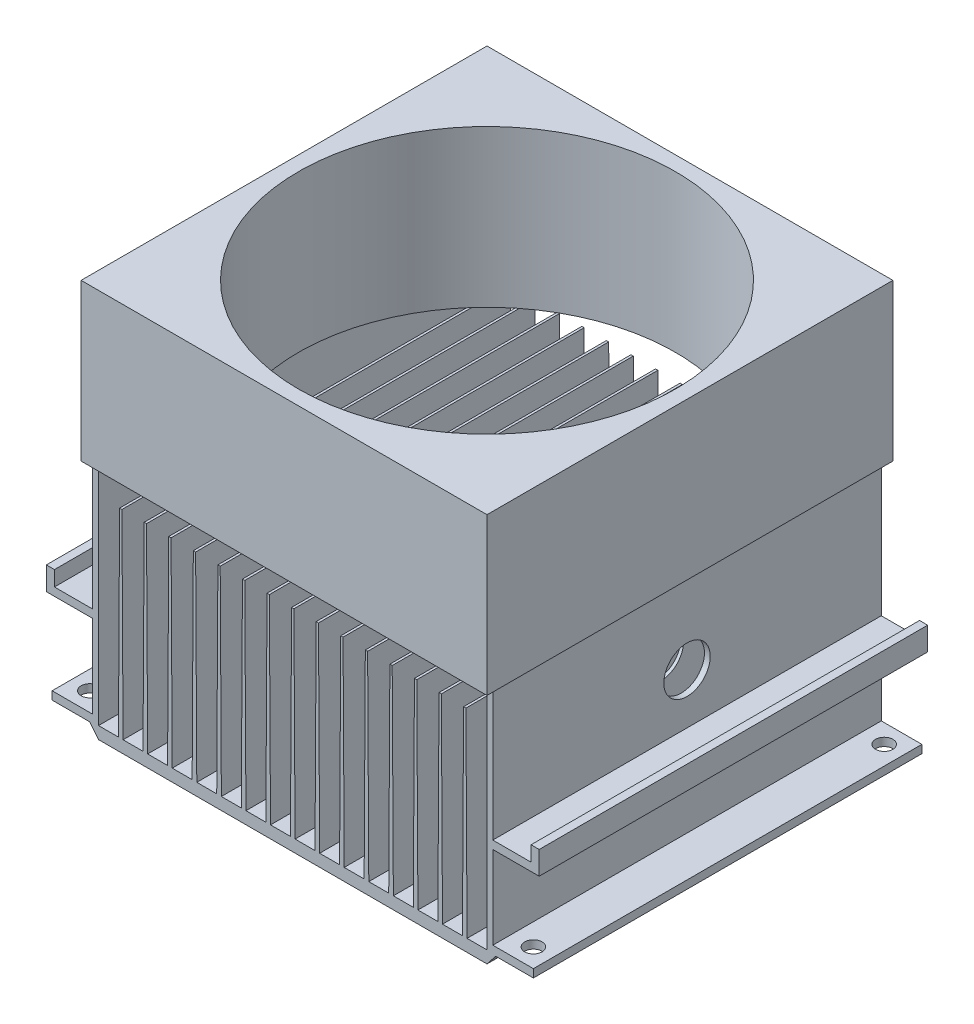
SolidWorks part; units mm, degrees
material "1060 Alloy"
ref_plane "Front Plane" through (0, 0, 0) normal (0, 0, 1) x (1, 0, 0)
ref_plane "Top Plane" through (0, 0, 0) normal (0, 1, 0) x (1, 0, 0)
ref_plane "Right Plane" through (0, 0, 0) normal (1, 0, 0) x (0, 0, -1)
sketch "Sketch1" plane through (0, 0, 0) normal (0, 0, 1) x (1, 0, 0)
  line L0 (0, 0) -> (0, 21.4242) construction
  line L1 (-33.5, 0) -> (33.5, 0)
  line L2 (33.5, 0) -> (35, 1.9)
  line L3 (35, 1.9) -> (41.5, 1.9)
  line L4 (41.5, 1.9) -> (41.5, 3.3)
  line L5 (41.5, 3.3) -> (34.5, 3.3)
  line L6 (34.5, 3.3) -> (34.5, 17.6)
  line L7 (34.5, 41.6) -> (33.5, 41.6)
  line L8 (33.5, 41.6) -> (33.5, 2.1)
  line L9 (33.5, 2.1) -> (30.0625, 2.1)
  line L10 (30.0625, 2.1) -> (29.8625, 36.4)
  line L11 (29.8625, 36.4) -> (29.4625, 36.4)
  line L12 (29.4625, 36.4) -> (29.2625, 2.1)
  line L13 (29.2625, 2.1) -> (25.825, 2.1)
  line L14 (29.4625, 36.4) -> (29.4625, 2.1) construction
  line L15 (29.4625, 2.1) -> (29.2625, 2.1) construction
  line L16 (29.8625, 36.4) -> (29.8625, 2.1) construction
  line L17 (29.8625, 2.1) -> (30.0625, 2.1) construction
  line L18 (29.4625, 2.1) -> (29.8625, 2.1) construction
  line L19 (34.5, 17.6) -> (42.5, 17.6)
  line L20 (42.5, 17.6) -> (42.5, 21.6)
  line L21 (42.5, 21.6) -> (41.1, 21.6)
  line L22 (41.1, 21.6) -> (41.1, 19)
  line L23 (41.1, 19) -> (34.5, 19)
  line L24 (34.5, 19) -> (34.5, 41.6)
  line L25 (34.5, 19) -> (34.5, 17.6) construction
  line L26 (34.5, 3.3) -> (34.5, 2.1) construction
  line L28 (34.5, 2.1) -> (33.5, 2.1) construction
  line L29 (25.825, 2.1) -> (25.625, 36.4)
  line L30 (25.225, 36.4) -> (25.025, 2.1)
  line L31 (25.625, 36.4) -> (25.225, 36.4)
  line L32 (25.025, 2.1) -> (21.5875, 2.1)
  line L33 (21.5875, 2.1) -> (21.3875, 36.4)
  line L34 (20.9875, 36.4) -> (20.7875, 2.1)
  line L35 (21.3875, 36.4) -> (20.9875, 36.4)
  line L36 (20.7875, 2.1) -> (17.35, 2.1)
  line L37 (17.35, 2.1) -> (17.15, 36.4)
  line L38 (16.75, 36.4) -> (16.55, 2.1)
  line L39 (17.15, 36.4) -> (16.75, 36.4)
  line L40 (16.55, 2.1) -> (13.1125, 2.1)
  line L41 (13.1125, 2.1) -> (12.9125, 36.4)
  line L42 (12.5125, 36.4) -> (12.3125, 2.1)
  line L43 (12.9125, 36.4) -> (12.5125, 36.4)
  line L44 (12.3125, 2.1) -> (8.875, 2.1)
  line L45 (8.875, 2.1) -> (8.675, 36.4)
  line L46 (8.275, 36.4) -> (8.075, 2.1)
  line L47 (8.675, 36.4) -> (8.275, 36.4)
  line L48 (8.075, 2.1) -> (4.6375, 2.1)
  line L49 (4.6375, 2.1) -> (4.4375, 36.4)
  line L50 (4.0375, 36.4) -> (3.8375, 2.1)
  line L51 (4.4375, 36.4) -> (4.0375, 36.4)
  line L52 (0.4, 2.1) -> (0, 2.1) construction
  line L53 (0, 2.1) -> (-0.4, 2.1) construction
  line L54 (3.8375, 2.1) -> (0.4, 2.1)
  line L55 (0.4, 2.1) -> (0.2, 36.4)
  line L56 (-0.2, 36.4) -> (-0.4, 2.1)
  line L57 (0.2, 36.4) -> (-0.2, 36.4)
  line L58 (-3.8375, 2.1) -> (-0.4, 2.1)
  line L59 (-4.0375, 36.4) -> (-3.8375, 2.1)
  line L60 (-4.4375, 36.4) -> (-4.0375, 36.4)
  line L61 (-4.6375, 2.1) -> (-4.4375, 36.4)
  line L62 (-8.075, 2.1) -> (-4.6375, 2.1)
  line L63 (-8.275, 36.4) -> (-8.075, 2.1)
  line L64 (-8.675, 36.4) -> (-8.275, 36.4)
  line L65 (-8.875, 2.1) -> (-8.675, 36.4)
  line L66 (-12.3125, 2.1) -> (-8.875, 2.1)
  line L67 (-12.5125, 36.4) -> (-12.3125, 2.1)
  line L68 (-12.9125, 36.4) -> (-12.5125, 36.4)
  line L69 (-13.1125, 2.1) -> (-12.9125, 36.4)
  line L70 (-16.55, 2.1) -> (-13.1125, 2.1)
  line L71 (-16.75, 36.4) -> (-16.55, 2.1)
  line L72 (-17.15, 36.4) -> (-16.75, 36.4)
  line L73 (-17.35, 2.1) -> (-17.15, 36.4)
  line L74 (-20.7875, 2.1) -> (-17.35, 2.1)
  line L75 (-20.9875, 36.4) -> (-20.7875, 2.1)
  line L76 (-21.3875, 36.4) -> (-20.9875, 36.4)
  line L77 (-21.5875, 2.1) -> (-21.3875, 36.4)
  line L78 (-25.025, 2.1) -> (-21.5875, 2.1)
  line L79 (-25.225, 36.4) -> (-25.025, 2.1)
  line L80 (-25.625, 36.4) -> (-25.225, 36.4)
  line L81 (-25.825, 2.1) -> (-25.625, 36.4)
  line L82 (-29.2625, 2.1) -> (-25.825, 2.1)
  line L83 (-29.4625, 36.4) -> (-29.2625, 2.1)
  line L84 (-29.8625, 36.4) -> (-29.4625, 36.4)
  line L85 (-30.0625, 2.1) -> (-29.8625, 36.4)
  line L86 (-33.5, 2.1) -> (-30.0625, 2.1)
  line L87 (-33.5, 41.6) -> (-33.5, 2.1)
  line L88 (-34.5, 41.6) -> (-33.5, 41.6)
  line L89 (-34.5, 19) -> (-34.5, 41.6)
  line L90 (-41.1, 19) -> (-34.5, 19)
  line L91 (-41.1, 21.6) -> (-41.1, 19)
  line L92 (-42.5, 21.6) -> (-41.1, 21.6)
  line L93 (-42.5, 17.6) -> (-42.5, 21.6)
  line L94 (-34.5, 17.6) -> (-42.5, 17.6)
  line L95 (-34.5, 3.3) -> (-34.5, 17.6)
  line L96 (-41.5, 3.3) -> (-34.5, 3.3)
  line L97 (-41.5, 1.9) -> (-41.5, 3.3)
  line L98 (-35, 1.9) -> (-41.5, 1.9)
  line L99 (-33.5, 0) -> (-35, 1.9)
  point P96 (0, 0)
  dimension "D1" = 41.5
  dimension "D2" = 41.6
  dimension "D3" = 2.1
  dimension "D4" = 1.4
  dimension "D5" = 1
  dimension "D6" = 7
  dimension "D7" = 85
  dimension "D8" = 0.4
  dimension "D9" = 0.8
  dimension "D10" = 67
  dimension "D11" = 36.4
  dimension "D12" = 83
  dimension "D14" = 6.5
  dimension "D15" = 3.3
  dimension "D16" = 4
  dimension "D13" = 8
extrude "Heatsink" add sketch "Sketch1" against normal blind 67
sketch "Sketch3" plane through (0, 41.6, 0) normal (0, 1, 0) x (1, 0, 0)
  line L0 (0, 0) -> (0, 1.5243) construction
  line L1 (-35, 68.5) -> (35, 68.5)
  line L2 (0, 0) -> (2.5943, 0) construction
  line L3 (17.5, -1.5) -> (17.5, 0) construction
  line L4 (-35, 68.5) -> (-35, -1.5)
  line L5 (-35, -1.5) -> (0, -1.5)
  line L6 (35, 68.5) -> (35, -1.5)
  line L7 (0, -1.5) -> (35, -1.5)
  line L8 (17.5, 68.5) -> (17.5, 67) construction
  line L9 (16.55, 67) -> (13.1125, 67) construction
  line L10 (35, 33.5) -> (-35, 33.5) construction
  circle A0 centre (0, 33.5) radius 32.5
  dimension "D2" = 65
  dimension "D1" = 70
extrude "Fan" add sketch "Sketch3" along normal blind 27 separate body
sketch "Sketch4" plane through (0, 1.9, 0) normal (0, -1, 0) x (1, 0, 0)
  line L0 (38.25, -3.25) -> (35, -3.25) construction
  line L3 (38.25, -3.25) -> (38.25, 0) construction
  line L4 (35, 0) -> (41.5, 0) construction
  line L5 (35, -67) -> (35, 0) construction
  line L6 (38.25, -3.25) -> (41.5, -3.25) construction
  line L7 (41.5, -67) -> (41.5, 0) construction
  line L8 (0, 0) -> (0, -33.5) construction
  line L9 (0, -33.5) -> (0, -67) construction
  line L10 (-33.5, -67) -> (33.5, -67) construction
  line L11 (0, -33.5) -> (24.0415, -33.5) construction
  circle A0 centre (38.25, -3.25) radius 1.5
  circle A1 centre (-38.25, -3.25) radius 1.5
  circle A2 centre (38.25, -63.75) radius 1.5
  circle A3 centre (-38.25, -63.75) radius 1.5
  point P27 (50.5248, -10.3477)
  dimension "D1" = 3
  dimension "D2" = 76.5
  dimension "D3" = 60.5
  dimension "D4" = 6.5
  dimension "D5" = 3.25
extrude "Mounting Holes Cut-Extrude1" cut sketch "Sketch4" against normal up to surface (1.4 mm away) up to face at (-38, 3.3, -33.5)
sketch "Sketch6" plane through (34.5, 0, 0) normal (1, 0, 0) x (0, 0, -1)
  line L0 (0, 19) -> (84.4752, 19) construction
  line L1 (67, 19) -> (0, 19) construction
  line L2 (14.0441, 36.4) -> (96.243, 36.4) construction
  line L3 (67, 36.4) -> (0, 36.4) construction
  line L4 (0, 27.7) -> (33.5, 27.7) construction
  line L5 (0, 19) -> (0, 41.6) construction
  line L6 (33.5, 27.7) -> (67, 27.7) construction
  line L7 (67, 19) -> (67, 41.6) construction
  line L8 (33.5, 27.7) -> (33.5, 19) construction
  line L9 (33.5, 27.7) -> (33.5, 36.4) construction
  circle A0 centre (33.5, 27.7) radius 4
  dimension "D1" = 8
extrude "U-Arm Shaft Cut-Extrude2" cut sketch "Sketch6" against normal up to surface (69 mm away) up to face at (-34.5, 30.3, -33.5)
equation "\"D1@Sketch1\"=83/2"
